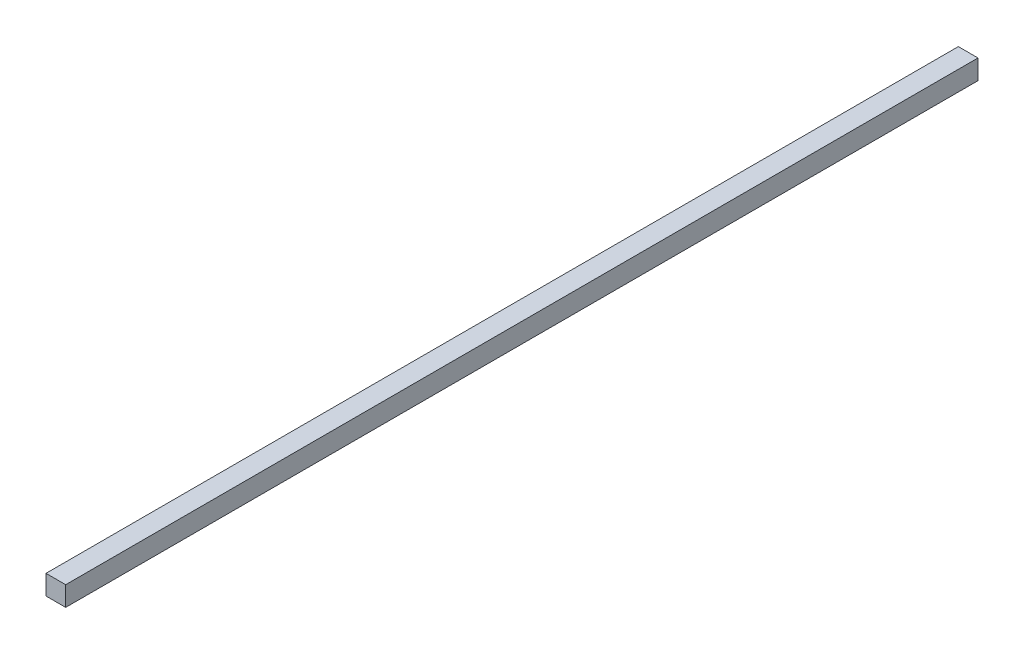
SolidWorks part; units mm, degrees
ref_plane "Front Plane" through (0, 0, 0) normal (0, 0, 1) x (1, 0, 0)
ref_plane "Top Plane" through (0, 0, 0) normal (0, 1, 0) x (1, 0, 0)
ref_plane "Right Plane" through (0, 0, 0) normal (1, 0, 0) x (0, 0, -1)
sketch "Sketch1" plane through (0, 0, 0) normal (0, 0, 1) x (1, 0, 0)
  line L1 (0, 4.8) -> (4.8, 4.8)
  line L2 (0, 4.8) -> (0, 0)
  line L3 (0, 0) -> (4.8, 0)
  line L4 (4.8, 4.8) -> (4.8, 0)
  point P4 (0, 0)
  dimension "D1" = 4.8
  dimension "D2" = 4.8
extrude "Boss-Extrude1" add sketch "Sketch1" along normal blind 222.5
